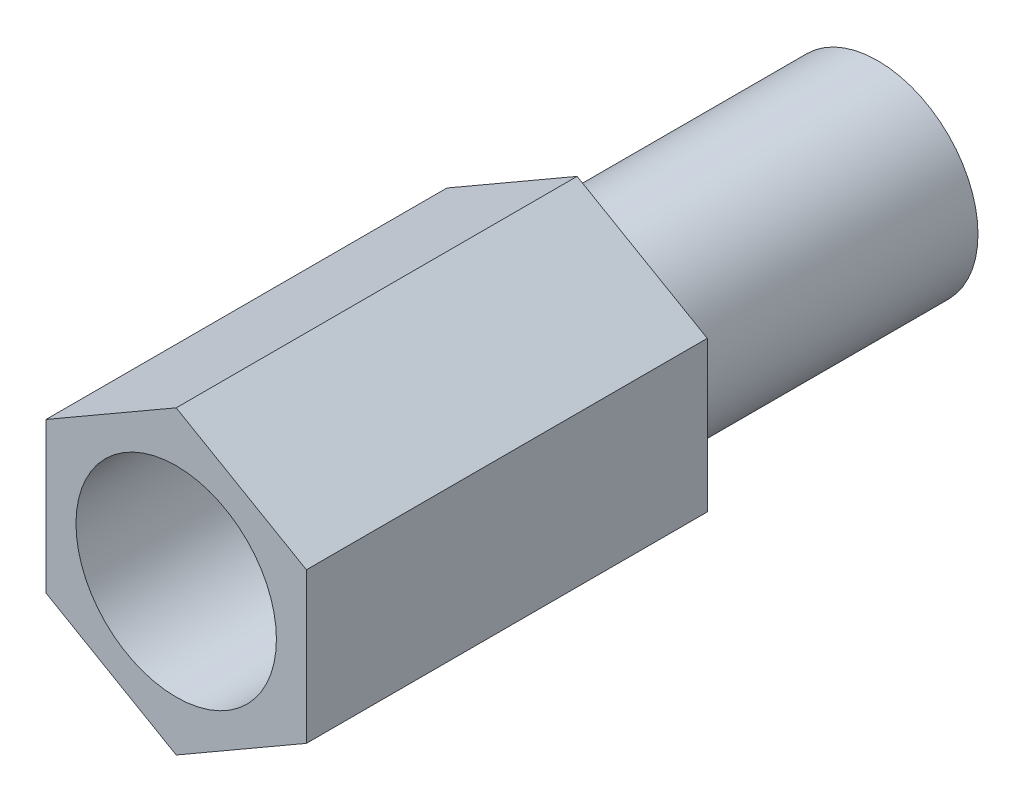
SolidWorks part; units mm, degrees
material "铜"
ref_plane "前视基准面" through (0, 0, 0) normal (0, 0, 1) x (1, 0, 0)
ref_plane "上视基准面" through (0, 0, 0) normal (0, 1, 0) x (1, 0, 0)
ref_plane "右视基准面" through (0, 0, 0) normal (1, 0, 0) x (0, 0, -1)
sketch "草图1" plane through (0, 0, 0) normal (0, 0, 1) x (1, 0, 0)
  line L1 (0, 3) -> (-2.5981, 1.5)
  line L2 (-2.5981, 1.5) -> (-2.5981, -1.5)
  line L3 (-2.5981, -1.5) -> (0, -3)
  line L4 (0, -3) -> (2.5981, -1.5)
  line L5 (2.5981, -1.5) -> (2.5981, 1.5)
  line L6 (2.5981, 1.5) -> (0, 3)
  circle A0 centre (0, 0) radius 2.5981 construction
  dimension "D1" = 6
extrude "凸台-拉伸1" add sketch "草图1" along normal blind 8
sketch "草图2" plane through (0, 0, 8) normal (0, 0, 1) x (1, 0, 0)
  circle A0 centre (0, 0) radius 2
  dimension "D1" = 4
extrude "切除-拉伸1" cut sketch "草图2" against normal blind 6
sketch "草图3" plane through (0, 0, 0) normal (0, 0, -1) x (-1, 0, 0)
  circle A0 centre (0, 0) radius 2
  dimension "D1" = 4
extrude "凸台-拉伸2" add sketch "草图3" along normal blind 6
